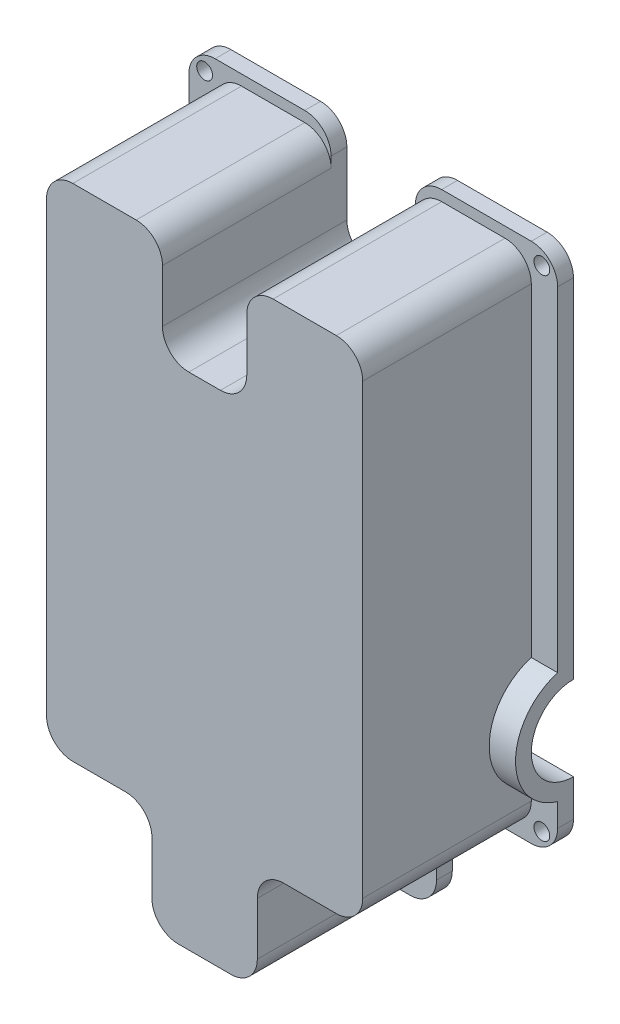
SolidWorks part; units mm, degrees
ref_plane "Front Plane" through (0, 0, 0) normal (0, 0, 1) x (1, 0, 0)
ref_plane "Top Plane" through (0, 0, 0) normal (0, 1, 0) x (1, 0, 0)
ref_plane "Right Plane" through (0, 0, 0) normal (1, 0, 0) x (0, 0, -1)
sketch "Sketch1" plane through (0, 0, 0) normal (0, 0, 1) x (1, 0, 0)
  line L1 (35, -59.5) -> (-35, -59.5)
  line L2 (35, -59.5) -> (35, 59.5)
  line L3 (35, 59.5) -> (-35, 59.5)
  line L4 (-35, -59.5) -> (-35, 59.5)
  line L5 (35, -59.5) -> (-35, 59.5) construction
  line L6 (35, 59.5) -> (-35, -59.5) construction
  point P0 (0, 0)
  dimension "D1" = 70
  dimension "D2" = 119
extrude "Boss-Extrude1" add sketch "Sketch1" along normal blind 35
sketch "Sketch2" plane through (35, 0, 0) normal (1, 0, 0) x (0, 0, -1)
  line L0 (0, -59.5) -> (0, 59.5) construction
  line L1 (-35, -59.5) -> (0, -59.5) construction
  circle A0 centre (0, -19.5) radius 8
  dimension "D1" = 16
  dimension "D2" = 40
extrude "Cut-Extrude1" cut sketch "Sketch2" against normal blind 8
sketch "Sketch3" plane through (-35, 0, 0) normal (-1, 0, 0) x (0, 0, 1)
  line L0 (0, 59.5) -> (0, -59.5) construction
  circle A0 centre (0, 19.5) radius 8
  dimension "D1" = 16
  dimension "D2" = 79
extrude "Cut-Extrude2" cut sketch "Sketch3" against normal blind 8
sketch "Sketch4" plane through (0, 0, 0) normal (0, 0, -1) x (-1, 0, 0)
  line L0 (-35, -11.5) -> (-35, 59.5) construction
  line L1 (-13, 54.5) -> (-27, 54.5)
  line L2 (-13, 54.5) -> (-13, -34.5)
  line L3 (-13, -34.5) -> (-27, -34.5)
  line L4 (-27, 54.5) -> (-27, -34.5)
  line L5 (7, 34.5) -> (-7, 34.5)
  line L6 (7, 34.5) -> (7, -54.5)
  line L7 (7, -54.5) -> (-7, -54.5)
  line L8 (-7, 34.5) -> (-7, -54.5)
  line L9 (13, 54.5) -> (27, 54.5)
  line L10 (13, 54.5) -> (13, -34.5)
  line L11 (13, -34.5) -> (27, -34.5)
  line L12 (27, 54.5) -> (27, -34.5)
  line L13 (35, 59.5) -> (35, 27.5) construction
  line L14 (35, -59.5) -> (-35, -59.5) construction
  line L15 (-35, 59.5) -> (35, 59.5) construction
  line M13 (27, 11.5) -> (27, 27.5)
  line M19 (-27, -11.5) -> (-27, -27.5)
  dimension "D1" = 8
  dimension "D2" = 8
  dimension "D3" = 14
  dimension "D4" = 14
  dimension "D5" = 14
  dimension "D6" = 6
  dimension "D7" = 25
  dimension "D8" = 5
  dimension "D9" = 89
  dimension "D10" = 25
extrude "Cut-Extrude3" cut sketch "Sketch4" against normal blind 32 contours L1 L4 L3 L2 M19 | L5 L8 L7 L6 | L12 L9 L10 L11 M13
sketch "Sketch5" plane through (7, 0, 0) normal (-1, 0, 0) x (0, 0, 1)
  line L0 (0, 27.5) -> (0, 11.5)
  arc A0 (0, 11.5) -> (0, 27.5) centre (0, 19.5) ccw construction
  arc A1 (0, 11.5) -> (0, 27.5) centre (0, 19.5) ccw
extrude "Cut-Extrude4" cut sketch "Sketch5" against normal up to next
sketch "Sketch6" plane through (-7, 0, 0) normal (1, 0, 0) x (0, 0, -1)
  line L0 (0, -11.5) -> (0, -27.5)
  arc A0 (0, -11.5) -> (0, -27.5) centre (0, -19.5) ccw construction
  arc A1 (0, -11.5) -> (0, -27.5) centre (0, -19.5) ccw
extrude "Cut-Extrude5" cut sketch "Sketch6" against normal up to next
sketch "Sketch7" plane through (0, 0, 0) normal (0, 0, -1) x (-1, 0, 0)
  line L0 (0, 59.5) -> (0, -59.5) construction
  line L1 (-35, 59.5) -> (35, 59.5) construction
  line L2 (35, -59.5) -> (-35, -59.5) construction
  line L3 (35, -59.5) -> (35, -39.5)
  line L4 (-8, 59.5) -> (8, 59.5)
  line L5 (-8, 59.5) -> (-8, 39.5)
  line L6 (-8, 39.5) -> (8, 39.5)
  line L7 (8, 59.5) -> (8, 39.5)
  line L8 (-35, -59.5) -> (-12, -59.5)
  line L9 (-35, -59.5) -> (-35, -39.5)
  line L10 (-35, -39.5) -> (-12, -39.5)
  line L11 (-12, -59.5) -> (-12, -39.5)
  line L12 (35, -59.5) -> (12, -59.5)
  line L13 (12, -59.5) -> (12, -39.5)
  line L14 (35, -39.5) -> (12, -39.5)
  dimension "D1" = 16
  dimension "D2" = 20
  dimension "D3" = 23
  dimension "D4" = 20
extrude "Cut-Extrude7" cut sketch "Sketch7" against normal through all
sketch "Sketch11" plane through (35, 0, 0) normal (1, 0, 0) x (0, 0, -1)
  line L10 (-3, 59.5) -> (-35, 59.5)
  line L11 (-35, 59.5) -> (-35, -39.5)
  line L12 (-3, -39.5) -> (-3, -30.083)
  line L13 (-3, -8.917) -> (-3, 59.5)
  line L14 (-3, -39.5) -> (-3, -30.083)
  line L15 (-3, -8.917) -> (-3, 59.5)
  line L16 (-35, -39.5) -> (-3, -39.5)
  arc A3 (-3, -8.917) -> (-3, -30.083) centre (0, -19.5) ccw
  arc A4 (-3, -8.917) -> (-3, -30.083) centre (0, -19.5) ccw
  dimension "D1" = 3
extrude "Cut-Extrude8" cut sketch "Sketch11" against normal blind 5
sketch "Sketch12" plane through (0, -39.5, 0) normal (0, -1, 0) x (1, 0, 0)
  line L1 (30, 3) -> (12, 3)
  line L2 (30, 3) -> (30, 35)
  line L3 (30, 35) -> (12, 35)
  line L4 (12, 3) -> (12, 35)
extrude "Cut-Extrude9" cut sketch "Sketch12" against normal blind 2
sketch "Sketch13" plane through (0, -59.5, 0) normal (0, -1, 0) x (1, 0, 0)
  line L1 (12, 3) -> (-12, 3)
  line L2 (12, 3) -> (12, 35)
  line L3 (12, 35) -> (-12, 35)
  line L4 (-12, 3) -> (-12, 35)
extrude "Cut-Extrude10" cut sketch "Sketch13" against normal blind 2
sketch "Sketch14" plane through (0, -39.5, 0) normal (0, -1, 0) x (1, 0, 0)
  line L1 (-12, 3) -> (-35, 3)
  line L2 (-12, 3) -> (-12, 35)
  line L3 (-12, 35) -> (-35, 35)
  line L4 (-35, 3) -> (-35, 35)
extrude "Cut-Extrude11" cut sketch "Sketch14" against normal blind 2
sketch "Sketch15" plane through (-12, 0, 0) normal (-1, 0, 0) x (0, 0, 1)
  line L1 (35, -57.5) -> (3, -57.5)
  line L2 (35, -57.5) -> (35, -37.5)
  line L3 (35, -37.5) -> (3, -37.5)
  line L4 (3, -57.5) -> (3, -37.5)
extrude "Cut-Extrude12" cut sketch "Sketch15" against normal blind 2
sketch "Sketch16" plane through (12, 0, 0) normal (1, 0, 0) x (0, 0, -1)
  line L1 (-3, -57.5) -> (-35, -57.5)
  line L2 (-3, -57.5) -> (-3, -37.5)
  line L3 (-3, -37.5) -> (-35, -37.5)
  line L4 (-35, -57.5) -> (-35, -37.5)
extrude "Cut-Extrude13" cut sketch "Sketch16" against normal blind 2
sketch "Sketch17" plane through (0, 59.5, 0) normal (0, 1, 0) x (1, 0, 0)
  line L1 (30, -3) -> (-35, -3)
  line L2 (30, -3) -> (30, -35)
  line L3 (30, -35) -> (-35, -35)
  line L4 (-35, -3) -> (-35, -35)
extrude "Cut-Extrude15" cut sketch "Sketch17" against normal blind 2
sketch "Sketch18" plane through (0, 39.5, 0) normal (0, 1, 0) x (1, 0, 0)
  line L1 (-8, -3) -> (8, -3)
  line L2 (-8, -3) -> (-8, -35)
  line L3 (-8, -35) -> (8, -35)
  line L4 (8, -3) -> (8, -35)
extrude "Cut-Extrude16" cut sketch "Sketch18" against normal blind 2
sketch "Sketch19" plane through (-35, 0, 0) normal (-1, 0, 0) x (0, 0, 1)
  line L0 (3, 57.5) -> (35, 57.5)
  line L3 (3, -37.5) -> (35, -37.5)
  line L5 (35, 57.5) -> (35, -37.5)
  line L11 (3, 59.5) -> (3, 30.083)
  line L12 (3, 8.917) -> (3, -39.5)
  line L13 (3, 57.5) -> (3, 30.083)
  line L14 (3, 8.917) -> (3, -37.5)
  arc A2 (3, 8.917) -> (3, 30.083) centre (0, 19.5) ccw
  arc A3 (3, 8.917) -> (3, 30.083) centre (0, 19.5) ccw
  dimension "D2" = 32
  dimension "D1" = 3
extrude "Cut-Extrude17" cut sketch "Sketch19" against normal blind 5
sketch "Sketch21" plane through (0, 0, 0) normal (0, 0, -1) x (-1, 0, 0)
  line L0 (-35, -11.5) -> (-35, 59.5) construction
  line L1 (-32, 56.5) -> (32, 56.5) construction
  line L2 (-32, 56.5) -> (-32, -36.5) construction
  line L3 (-32, -36.5) -> (32, -36.5) construction
  line L4 (32, 56.5) -> (32, -36.5) construction
  line L5 (-35, 59.5) -> (-8, 59.5) construction
  line L6 (35, 59.5) -> (35, 27.5) construction
  line L7 (35, -39.5) -> (12, -39.5) construction
  circle A0 centre (-32, 56.5) radius 1.5
  circle A1 centre (32, 56.5) radius 1.5
  circle A2 centre (-32, -36.5) radius 1.5
  circle A3 centre (32, -36.5) radius 1.5
  dimension "D5" = 3
  dimension "D1" = 3
  dimension "D2" = 3
  dimension "D3" = 3
  dimension "D4" = 3
extrude "Cut-Extrude18" cut sketch "Sketch21" against normal blind 10
fillet "Fillet1" radius 5 12 edges at (-30, 57.5, 19) (-8, 57.5, 19) (-8, 37.5, 19) (8, 37.5, 19) (8, 57.5, 19) (30, 57.5, 19) (30, -37.5, 19) (10, -37.5, 19) (10, -57.5, 19) (-10, -37.5, 19) (-30, -37.5, 19) (-10, -57.5, 19)
fillet "Fillet2" radius 5 10 edges at (35, 59.5, 1.5) (8, 59.5, 1.5) (-8, 59.5, 1.5) (-35, 59.5, 1.5) (-35, -39.5, 1.5) (-12, -39.5, 1.5) (-12, -59.5, 1.5) (12, -59.5, 1.5) (12, -39.5, 1.5) (35, -39.5, 1.5)
